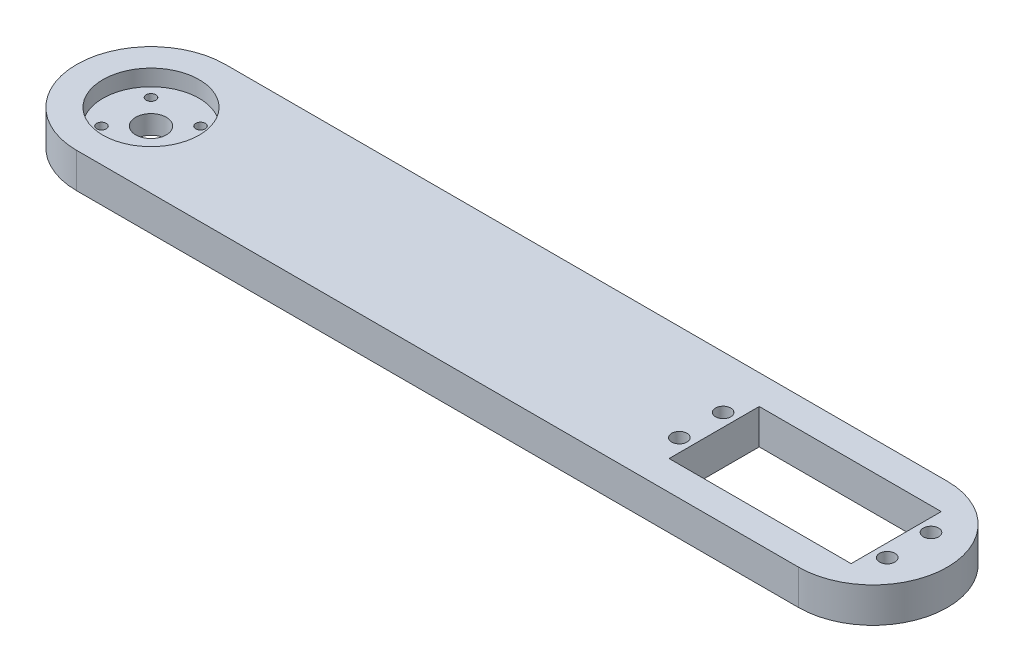
SolidWorks part; units mm, degrees
ref_plane "Piano frontale" through (0, 0, 0) normal (0, 0, 1) x (1, 0, 0)
ref_plane "Piano superiore" through (0, 0, 0) normal (0, 1, 0) x (1, 0, 0)
ref_plane "Piano destro" through (0, 0, 0) normal (1, 0, 0) x (0, 0, -1)
sketch "Schizzo1" plane through (0, 0, 0) normal (0, 1, 0) x (1, 0, 0)
  line L0 (0, -80.5161) -> (0, 90.1505) construction
  line L1 (-159.3118, 0) -> (168.6022, 0) construction
  line L2 (0, 0) -> (165, 0) construction
  line L3 (0, 17) -> (165, 17)
  line L4 (0, -17) -> (165, -17)
  arc A0 (0, 17) -> (0, -17) centre (0, 0) ccw
  arc A1 (165, -17) -> (165, 17) centre (165, 0) ccw
  point P7 (82.5, 0)
  dimension "D1" = 17
  dimension "D2" = 165
extrude "Estrusione-Estrusione1" add sketch "Schizzo1" along normal blind 8
sketch "Schizzo2" plane through (0, 0, 0) normal (0, -1, 0) x (1, 0, 0)
  line L0 (0, 0) -> (182, 0) construction
  line L1 (128.7, 10.3) -> (170.3, 10.3)
  line L2 (128.7, 10.3) -> (128.7, -10.3)
  line L3 (128.7, -10.3) -> (170.3, -10.3)
  line L4 (170.3, 10.3) -> (170.3, -10.3)
  circle A0 centre (0, 0) radius 3.5
  arc A1 (165, -17) -> (165, 17) centre (165, 0) ccw construction
  dimension "D1" = 7
  dimension "D2" = 128.7
  dimension "D3" = 41.6
  dimension "D4" = 20.6
  dimension "D5" = 10.3
extrude "Taglio-Estrusione1" cut sketch "Schizzo2" against normal through all and the other way through all
sketch "Schizzo3" plane through (0, 8, 0) normal (0, 1, 0) x (1, 0, 0)
  circle A0 centre (0, 0) radius 11
  dimension "D1" = 22
extrude "Taglio-Estrusione2" cut sketch "Schizzo3" against normal blind 3.7
sketch "Schizzo4" plane through (0, 4.3, 0) normal (0, 1, 0) x (1, 0, 0)
  line L0 (0, -9.3928) -> (0, 9.6775) construction
  line L1 (-9.863, 0) -> (9.492, 0) construction
  circle A0 centre (-5.66, 5.66) radius 1.1
  circle A1 centre (5.66, 5.66) radius 1.1
  circle A2 centre (5.66, -5.66) radius 1.1
  circle A3 centre (-5.66, -5.66) radius 1.1
  point P16 (0, 0)
  dimension "D1" = 2.2
  dimension "D2" = 5.66
  dimension "D3" = 5.66
  dimension "D5" = 11.32
  dimension "D6" = 11.32
  dimension "D4" = 4
extrude "Taglio-Estrusione3" cut sketch "Schizzo4" against normal blind 3
sketch "Schizzo5" plane through (0, 8, 0) normal (0, 1, 0) x (1, 0, 0)
  line L0 (0, 0) -> (180.1286, 0) construction
  line L1 (149.5, 10.3) -> (149.5, -10.3) construction
  line L2 (128.7, 10.3) -> (170.3, 10.3) construction
  line L3 (170.3, -10.3) -> (128.7, -10.3) construction
  circle A0 centre (125.75, 5) radius 1.75
  circle A2 centre (125.75, -5) radius 1.75
  circle A3 centre (173.25, -5) radius 1.75
  circle A4 centre (173.25, 5) radius 1.75
  dimension "D1" = 3.5
  dimension "D2" = 23.75
  dimension "D3" = 5
extrude "Taglio-Estrusione4" cut sketch "Schizzo5" against normal through all
